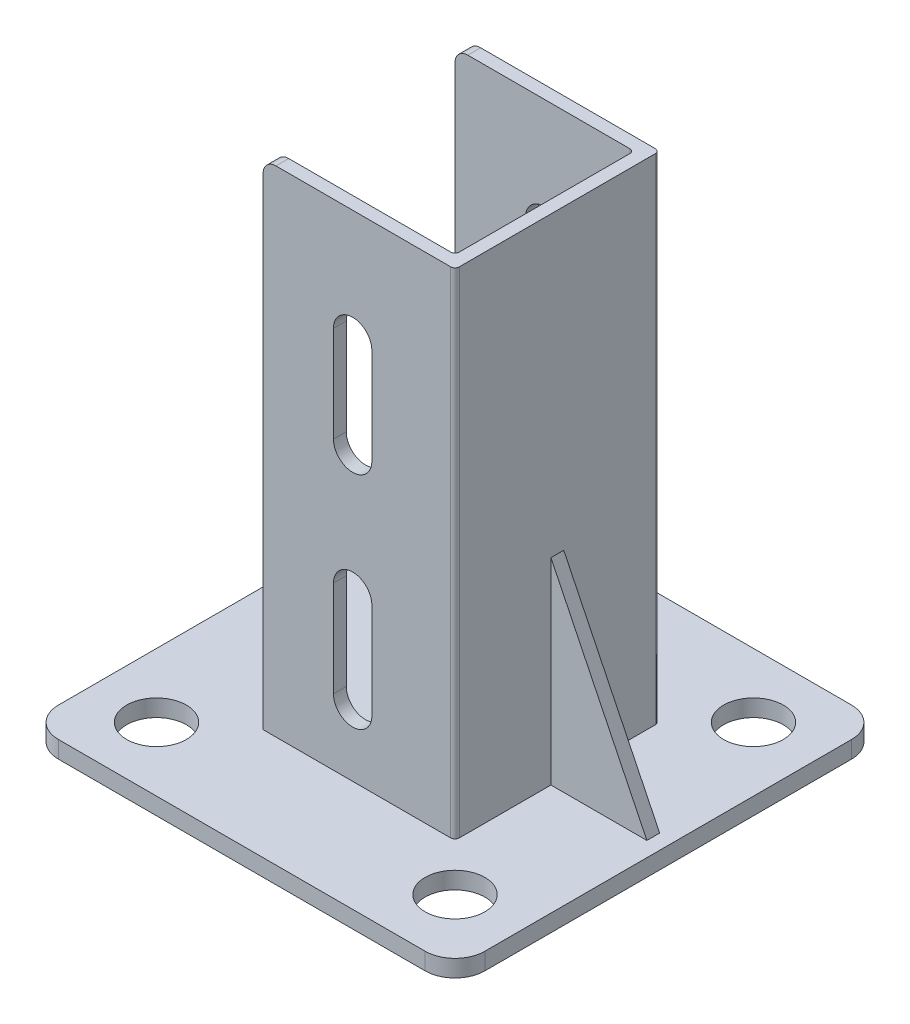
SolidWorks part; units mm, degrees
ref_plane "前视基准面" through (0, 0, 0) normal (0, 0, 1) x (1, 0, 0)
ref_plane "上视基准面" through (0, 0, 0) normal (0, 1, 0) x (1, 0, 0)
ref_plane "右视基准面" through (0, 0, 0) normal (1, 0, 0) x (0, 0, -1)
sketch "草图1" plane through (0, 0, 0) normal (0, 1, 0) x (1, 0, 0)
  line L1 (50, -50) -> (-50, -50)
  line L2 (50, -50) -> (50, 50)
  line L3 (50, 50) -> (-50, 50)
  line L4 (-50, -50) -> (-50, 50)
  line L5 (50, -50) -> (-50, 50) construction
  line L6 (50, 50) -> (-50, -50) construction
  line L11 (35, -35) -> (-35, 35) construction
  line L12 (35, 35) -> (-35, -35) construction
  circle A4 centre (-35, 35) radius 7
  circle A5 centre (35, 35) radius 7
  circle A6 centre (35, -35) radius 7
  circle A7 centre (-35, -35) radius 7
  point P0 (0, 0)
  point P6 (0, 0)
extrude "凸台-拉伸2" add sketch "草图1" along normal blind 4
fillet "圆角2" radius 7 4 edges at (50, 2, -50) (-50, 2, -50) (-50, 2, 50) (50, 2, 50)
sketch "草图3" plane through (0, 4, 0) normal (0, 1, 0) x (1, 0, 0)
  line L0 (-21, 21) -> (-21, 24)
  line L1 (21, -21) -> (-21, -21)
  line L2 (21, -21) -> (21, 21)
  line L3 (21, 21) -> (-21, 21)
  line L4 (-21, -21) -> (-21, 21)
  line L5 (21, -21) -> (-21, 21) construction
  line L6 (21, 21) -> (-21, -21) construction
  line L7 (-21, 24) -> (24, 24)
  line L8 (24, 24) -> (24, -24)
  line L9 (24, -24) -> (-21, -24)
  line L10 (-21, -24) -> (-21, -21)
  point P0 (0, 0)
extrude "凸台-拉伸3" add sketch "草图3" along normal blind 116 contours L10 L9 L8 L7 L0 L3 L2 L1
fillet "圆角3" radius 3 2 edges at (-21, 120, -22.5) (-21, 120, 22.5)
fillet "圆角4" radius 1 4 edges at (21, 62, -21) (21, 62, 21) (24, 62, -24) (24, 62, 24)
sketch "草图4" plane through (0, 0, -24) normal (0, 0, -1) x (-1, 0, 0)
  line L0 (0, 4) -> (0, 93.7618)
  line L1 (-43, 4) -> (43, 4) construction
  line L2 (0, 93.7618) -> (0, 71.2618) construction
  line L3 (4.5, 93.7618) -> (4.5, 71.2618)
  line L4 (-4.5, 93.7618) -> (-4.5, 71.2618)
  line L5 (0, 42.0267) -> (0, 19.5267) construction
  line L6 (4.5, 42.0267) -> (4.5, 19.5267)
  line L7 (-4.5, 42.0267) -> (-4.5, 19.5267)
  arc A0 (4.5, 93.7618) -> (-4.5, 93.7618) centre (0, 93.7618) ccw
  arc A1 (-4.5, 71.2618) -> (4.5, 71.2618) centre (0, 71.2618) ccw
  arc A2 (4.5, 42.0267) -> (-4.5, 42.0267) centre (0, 42.0267) ccw
  arc A3 (-4.5, 19.5267) -> (4.5, 19.5267) centre (0, 19.5267) ccw
  point P6 (0, 82.5118)
  point P13 (0, 30.7767)
extrude "切除-拉伸1" cut sketch "草图4" against normal blind 116 contours L6 A3 L7 A2 | L3 A1 L4 A0
sketch "草图6" plane through (0, 0, 0) normal (0, 0, 1) x (1, 0, 0)
  line L0 (24, 50.1885) -> (46.5, 4)
  line L2 (24, 120) -> (24, 4) construction
  line L3 (50, 4) -> (43, 4) construction
rib "筋1" sketch "草图6" sketch "草图6" thickness 3 extrusion direction parallel to sketch draft on no parameters "D1"=3
